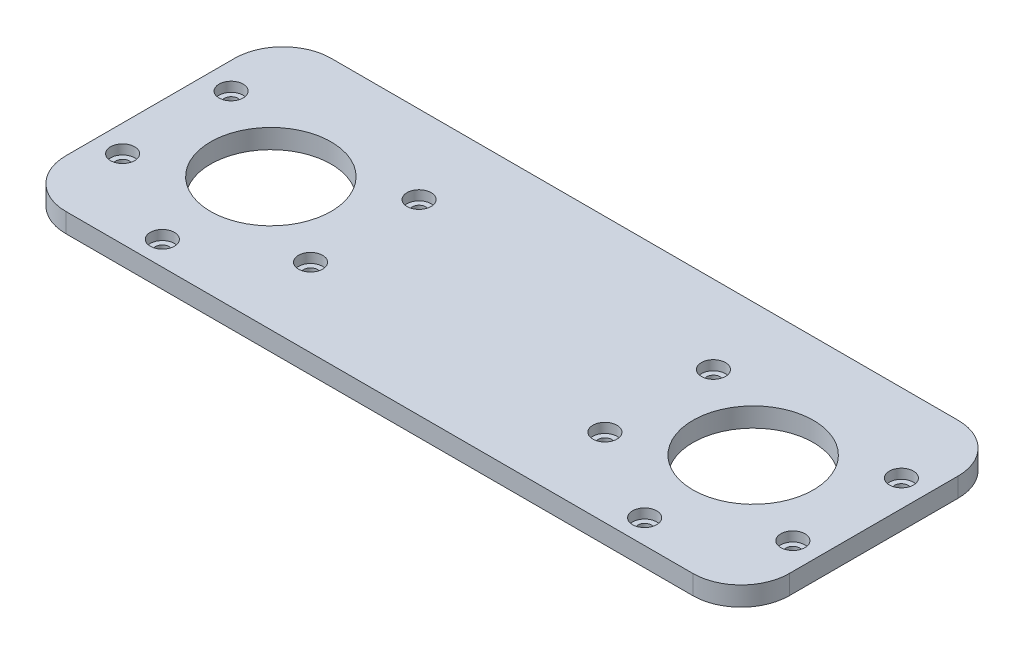
SolidWorks part; units mm, degrees
ref_plane "Front Plane" through (0, 0, 0) normal (0, 0, 1) x (1, 0, 0)
ref_plane "Top Plane" through (0, 0, 0) normal (0, 1, 0) x (1, 0, 0)
ref_plane "Right Plane" through (0, 0, 0) normal (1, 0, 0) x (0, 0, -1)
sketch "Sketch1" plane through (0, 0, 0) normal (0, 1, 0) x (1, 0, 0)
  line L0 (-50, 0) -> (50, 0) construction
  line L1 (-75, 27.5) -> (75, 27.5)
  line L2 (-75, 27.5) -> (-75, -27.5)
  line L3 (-75, -27.5) -> (75, -27.5)
  line L4 (75, 27.5) -> (75, -27.5)
  line L5 (0, 27.5) -> (0, 0) construction
  line L6 (0, 0) -> (0, -27.5) construction
  circle A0 centre (-50, 0) radius 12.5
  circle A1 centre (50, 0) radius 12.5
  dimension "D1" = 55
  dimension "D4" = 25
  dimension "D2" = 150
  dimension "D3" = 100
extrude "Boss-Extrude1" add sketch "Sketch1" along normal blind 4
sketch "Sketch2" plane through (0, 4, 0) normal (0, 1, 0) x (1, 0, 0)
  arc A0 (30.5144, -10.225) -> (30.5144, -12.275) centre (30.5144, -11.25) ccw construction
  arc A1 (30.5144, -10.225) -> (30.5144, -12.275) centre (30.5144, -11.25) ccw construction
  arc A2 (69.4856, -12.275) -> (69.4856, -10.225) centre (69.4856, -11.25) ccw construction
  arc A3 (69.4856, 10.225) -> (69.4856, 12.275) centre (69.4856, 11.25) ccw construction
  arc A4 (30.5144, 12.275) -> (30.5144, 10.225) centre (30.5144, 11.25) ccw construction
  arc A5 (50, -21.475) -> (50, -23.525) centre (50, -22.5) ccw construction
  arc A6 (69.4856, -12.275) -> (69.4856, -10.225) centre (69.4856, -11.25) ccw construction
  arc A7 (69.4856, 10.225) -> (69.4856, 12.275) centre (69.4856, 11.25) ccw construction
  arc A8 (30.5144, 12.275) -> (30.5144, 10.225) centre (30.5144, 11.25) ccw construction
  arc A9 (50, -21.475) -> (50, -23.525) centre (50, -22.5) ccw construction
  circle A10 centre (30.5144, 11.25) radius 1.4
  circle A11 centre (69.4856, 11.25) radius 1.4
  circle A12 centre (69.4856, -11.25) radius 1.4
  circle A13 centre (30.5144, -11.25) radius 1.4
  circle A14 centre (50, -22.5) radius 1.4
  dimension "D1" = 2.8
extrude "Cut-Extrude1" cut sketch "Sketch2" against normal through all
sketch "Sketch3" plane through (0, 4, 0) normal (0, 1, 0) x (1, 0, 0)
  circle A0 centre (30.5144, 11.25) radius 2.5
  circle A1 centre (30.5144, -11.25) radius 2.5
  circle A2 centre (50, -22.5) radius 2.5
  circle A3 centre (69.4856, -11.25) radius 2.5
  circle A4 centre (69.4856, 11.25) radius 2.5
  dimension "D1" = 5
extrude "Cut-Extrude3" cut sketch "Sketch3" against normal blind 2
mirror "Mirror1" about plane through (0, 0, 0) normal (1, 0, 0) of "Cut-Extrude3", "Cut-Extrude1"
fillet "Fillet1" radius 10 4 edges at (75, 2, -27.5) (75, 2, 27.5) (-75, 2, 27.5) (-75, 2, -27.5)
